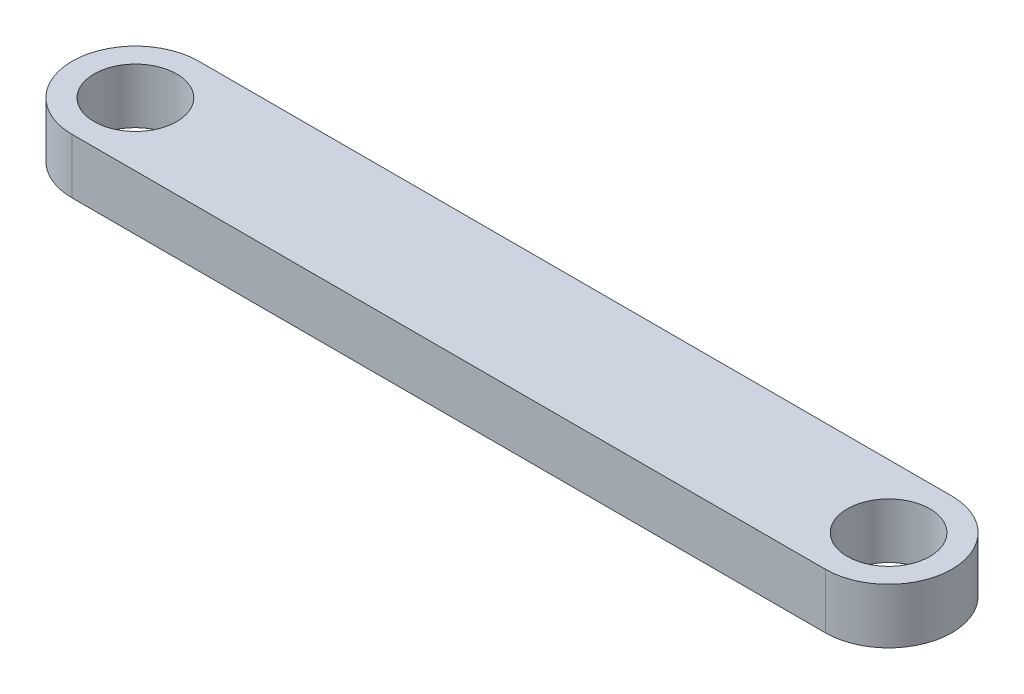
SolidWorks part; units mm, degrees
ref_plane "Front Plane" through (0, 0, 0) normal (0, 0, 1) x (1, 0, 0)
ref_plane "Top Plane" through (0, 0, 0) normal (0, 1, 0) x (1, 0, 0)
ref_plane "Right Plane" through (0, 0, 0) normal (1, 0, 0) x (0, 0, -1)
sketch "Sketch1" plane through (0, 0, 0) normal (0, 1, 0) x (1, 0, 0)
  line L0 (0, 0) -> (34.19, 0)
  line L1 (0, 0) -> (-34.19, 0)
  line L3 (-22.7989, -5.75) -> (22.7989, -5.75)
  line L5 (-22.7989, 5.75) -> (22.7989, 5.75)
  line L6 (-22.7989, -5.75) -> (-22.7989, 5.75)
  line L7 (22.7989, -5.75) -> (22.7989, 5.75)
  line L8 (-22.7989, 0) -> (22.7989, 0)
  line L9 (-34.19, -5.75) -> (34.19, -5.75)
  line L10 (-34.19, 5.75) -> (34.19, 5.75)
  circle A0 centre (-34.19, 0) radius 3.75
  circle A1 centre (34.19, 0) radius 3.75
  circle A2 centre (-34.19, 0) radius 5.75
  circle A3 centre (34.19, 0) radius 5.75
  dimension "D1" = 7.5
  dimension "D3" = 2
  dimension "D2" = 68.38
extrude "Boss-Extrude1" add sketch "Sketch1" along normal blind 5
